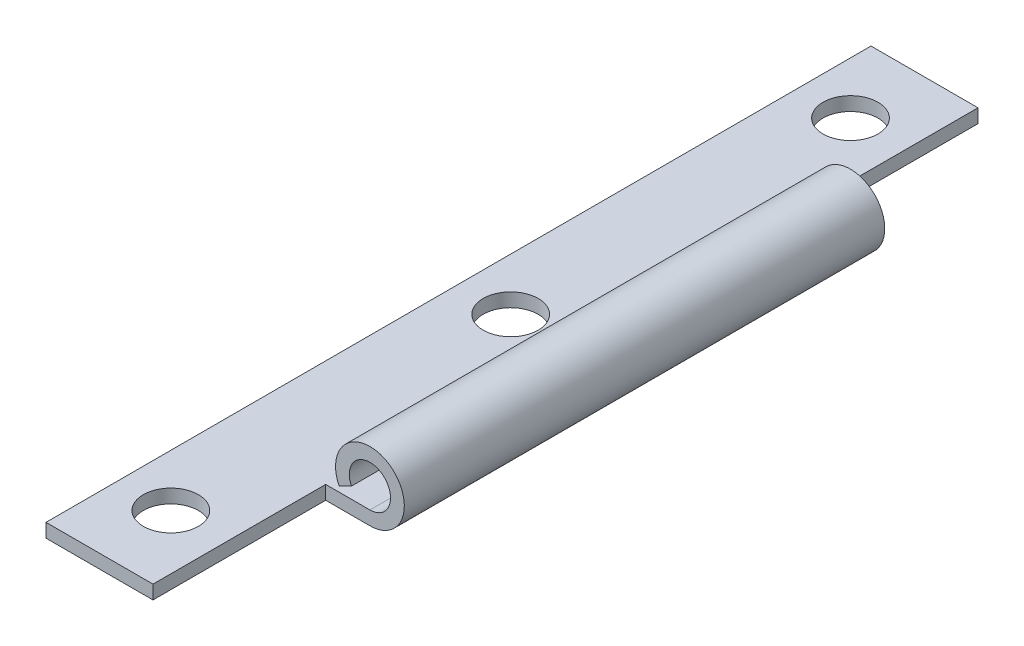
SolidWorks part; units mm, degrees
ref_plane "Front Plane" through (0, 0, 0) normal (0, 0, 1) x (1, 0, 0)
ref_plane "Top Plane" through (0, 0, 0) normal (0, 1, 0) x (1, 0, 0)
ref_plane "Right Plane" through (0, 0, 0) normal (1, 0, 0) x (0, 0, -1)
sketch "Sketch1" plane through (0, 0, 0) normal (0, 0, 1) x (1, 0, 0)
  line L0 (0, 0) -> (11, 0)
  arc A0 (11, 0) -> (8.7624, 1.385) centre (11, 2.5) ccw
sketch "Sketch3" plane through (0, 0, 0) normal (1, 0, 0) x (0, 0, -1)
  line L1 (0, 0) -> (-60, 0)
  line L2 (0, 0) -> (0, 1)
  line L3 (0, 1) -> (-60, 1)
  line L4 (-60, 0) -> (-60, 1)
sweep "Sweep1" add profiles "Sketch3" path "Sketch1"
sketch "Sketch4" plane through (0, 0, 0) normal (0, -1, 0) x (-1, 0, 0)
  line L0 (0, -30) -> (-29.3061, -30) construction
  line L1 (-7.781, 0.9676) -> (-7.781, 4.0341) construction
  line L4 (-15.8791, -61.6581) -> (-7.781, -61.6581)
  line L5 (-15.8791, -61.6581) -> (-15.8791, -47.4412)
  line L6 (-15.8791, -47.4412) -> (-7.781, -47.4412)
  line L7 (-7.781, -61.6581) -> (-7.781, -47.4412)
  line L8 (-15.8791, -61.6581) -> (-7.781, -47.4412) construction
  line L9 (-16.0413, 0.9676) -> (-7.781, 0.9676)
  line L10 (-16.0413, 0.9676) -> (-16.0413, -12.5)
  line L11 (-16.0413, -12.5) -> (-7.781, -12.5)
  line L12 (-7.781, 0.9676) -> (-7.781, -12.5)
  line L13 (-15.8791, -47.4412) -> (-7.781, -61.6581) construction
  point P1 (-11.8301, -54.5497)
extrude "Cut-Extrude1" cut sketch "Sketch4" against normal through all
sketch "Sketch5" plane through (0, 1, 0) normal (0, 1, 0) x (1, 0, 0)
  line L0 (0, -30) -> (-17.1075, -30) construction
  circle A0 centre (3.7946, -5.2859) radius 2
  circle A1 centre (3.7946, -54.7141) radius 2
  circle A2 centre (3.7946, -30) radius 2
extrude "Cut-Extrude2" cut sketch "Sketch5" against normal through all
